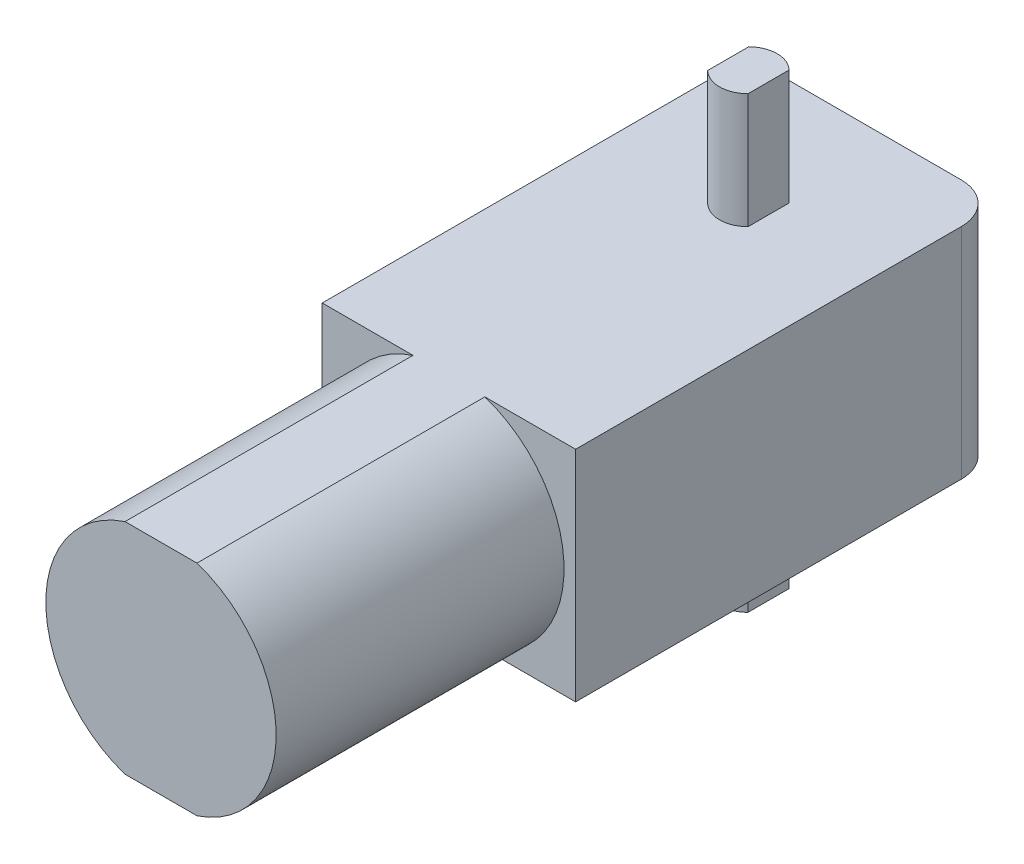
SolidWorks part; units mm, degrees
ref_plane "Front Plane" through (0, 0, 0) normal (1, 0, 0) x (0, 1, 0)
ref_plane "Top Plane" through (0, 0, 0) normal (0, 0, 1) x (0, 1, 0)
ref_plane "Right Plane" through (0, 0, 0) normal (0, 1, 0) x (-1, 0, 0)
sketch "Sketch1" plane through (0, 0, 0) normal (0, 0, 1) x (0, 1, 0)
  line L1 (0, 0) -> (19, 0)
  line L2 (0, 0) -> (0, 22)
  line L3 (0, 22) -> (19, 22)
  line L4 (19, 0) -> (19, 22)
  dimension "D1" = 19
  dimension "D2" = 22
extrude "Boss-Extrude1" add sketch "Sketch1" along normal blind 37
fillet "Fillet1" radius 3.5 2 edges at (-22, 9.5, 0) (0, 9.5, 0)
ref_plane "Plane1" through (0, 9.5, 0) normal (0, 1, 0) x (1, 0, 0)
sketch "Sketch2" plane through (0, 9.5, 0) normal (0, 1, 0) x (1, 0, 0)
  line L0 (-11, 0) -> (-11, -11) construction
  line L1 (-3.5, 0) -> (-18.5, 0) construction
  line L2 (-11, -11) -> (-12.75, -11) construction
  line L3 (-12.75, -11) -> (-12.75, -9.2146)
  line L4 (-12.75, -11) -> (-12.75, -12.7854)
  line L5 (-9.25, -11) -> (-9.25, -12.7854)
  line L6 (-9.25, -11) -> (-9.25, -9.2146)
  circle A0 centre (-11, -11) radius 2.5
  dimension "D2" = 5
  dimension "D1" = 11
  dimension "D3" = 1.75
extrude "Boss-Extrude2" add sketch "Sketch2" along normal mid plane 39 contours L6 A0 L3 L4 L5
sketch "Sketch4" plane through (0, 0, 37) normal (0, 0, 1) x (1, 0, 0)
  line L0 (-11, 19) -> (-11, 0) construction
  line L1 (0, 19) -> (-22, 19) construction
  line L2 (-12.75, 0) -> (-9.25, 0) construction
  line L3 (-22, 0) -> (0, 0) construction
  line L4 (-22, 0) -> (0, 0)
  line L5 (0, 19) -> (-22, 19)
  circle A0 centre (-11, 9.5) radius 10
  line M2 (-22, 0) -> (0, 0)
  line M4 (0, 19) -> (-22, 19)
  dimension "D1" = 20
extrude "Boss-Extrude3" add sketch "Sketch4" along normal blind 25 contours L5 L0 A0 M2 | L0 A0 L4 M4
